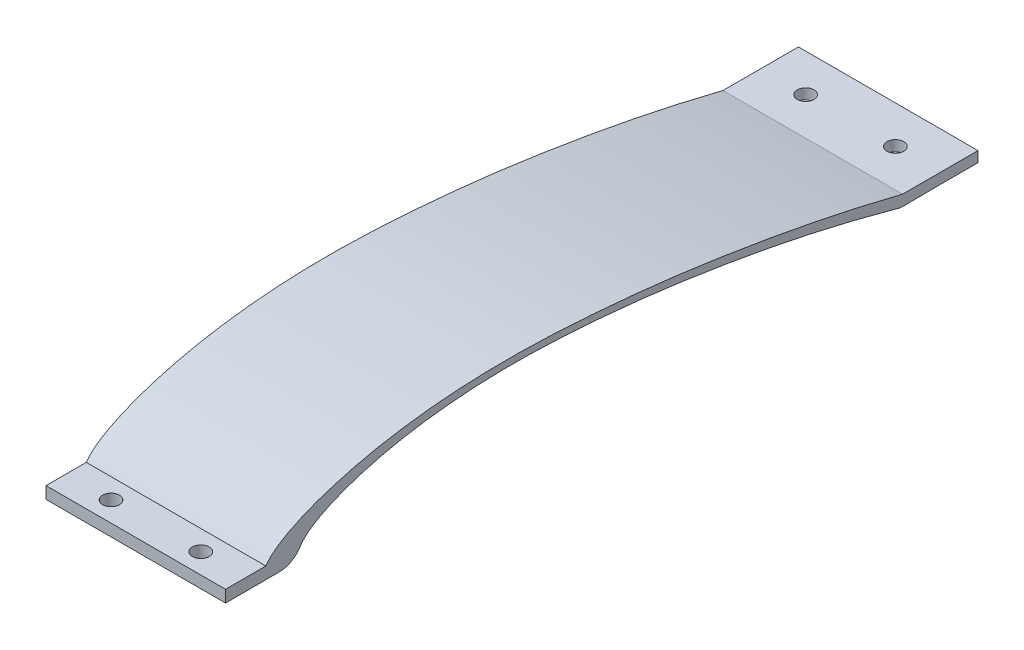
SolidWorks part; units mm, degrees
ref_plane "Front Plane" through (0, 0, 0) normal (0, 0, 1) x (1, 0, 0)
ref_plane "Top Plane" through (0, 0, 0) normal (0, 1, 0) x (1, 0, 0)
ref_plane "Right Plane" through (0, 0, 0) normal (1, 0, 0) x (0, 0, -1)
sketch "Sketch1" plane through (0, 0, 0) normal (1, 0, 0) x (0, 0, -1)
  arc A0 (-72.8391, -1.9598) -> (-75.0988, -4.0819) centre (-71.973, -5.1462) ccw
  spline S0 degree 3 poles (-72.8391, -1.9598) (-71.5193, -1.6011) (-70.1992, -1.244) (-67.557, -0.546) (-66.2347, -0.2062) (-62.2642, 0.7846) (-59.6128, 1.4106) (-54.3023, 2.6025) (-51.6431, 3.1671) (-46.3164, 4.2323) (-43.6489, 4.7326) (-38.3066, 5.6755) (-35.6319, 6.1188) (-30.2754, 6.9512) (-27.5936, 7.3389) (-19.535, 8.3999) (-14.1447, 8.9674) (-3.3295, 9.8307) (2.0964, 10.1191) (10.2856, 10.1582) (13.0238, 10.105) (17.1472, 9.8987) (18.5265, 9.8086) (21.2804, 9.5837) (22.6534, 9.449) (25.391, 9.133) (26.7556, 8.9518) (29.4761, 8.5409) (30.8319, 8.3111) (34.8834, 7.5325) (37.5622, 6.89) (41.5421, 5.7133) (42.8637, 5.2886) (45.453, 4.3284) (46.7237, 3.7932) (48.5836, 2.8839) (49.1954, 2.5618) (50.0944, 2.0358) (50.3918, 1.853) (50.9734, 1.4715) (51.2571, 1.2716) (51.8025, 0.8441) (52.0644, 0.6166) (52.5647, 0.1317) (52.8032, -0.1254) (53.2393, -0.6669) (53.439, -0.9532) (53.7755, -1.5678) (53.909, -1.8892) (54.0242, -2.4047) (54.0471, -2.5775) (54.0569, -2.9255) (54.0433, -3.1029) (53.9767, -3.4453) (53.9241, -3.6108) (53.7857, -3.9319) (53.7, -4.0864) (53.5079, -4.3759) (53.4007, -4.5126) (53.1684, -4.7729) (53.043, -4.8965) (52.653, -5.2424) (52.3721, -5.4443) (51.7759, -5.8001) (51.4587, -5.952) (50.8171, -6.2068) (50.4898, -6.312) (49.5008, -6.6028) (48.8306, -6.7592) (47.4738, -7.0165) (46.7908, -7.1162) (45.4268, -7.2745) (44.7442, -7.3333) (42.6956, -7.4788) (41.3287, -7.5388) (38.5934, -7.6044) (37.225, -7.6101) (34.4872, -7.5897) (33.1179, -7.5654) (30.3786, -7.4968) (29.0085, -7.4513) (26.2696, -7.338) (24.9006, -7.2706) (22.1627, -7.1323) (20.7937, -7.0629) (18.0556, -6.9306) (16.6864, -6.8663) (12.579, -6.6726) (9.8408, -6.5418) (4.364, -6.2908) (1.6253, -6.1723) (-3.8528, -5.9507) (-6.592, -5.8456) (-14.8094, -5.522) (-20.2871, -5.2904) (-31.2446, -4.8828) (-36.7244, -4.7045) (-47.6869, -4.4208) (-53.1687, -4.3186) (-61.392, -4.1963) (-64.1331, -4.1572) (-69.6157, -4.1049) (-72.3572, -4.0945) (-75.0988, -4.0819) knots 0 0 0 0 0.015625 0.015625 0.03125 0.03125 0.0625 0.0625 0.09375 0.09375 0.125 0.125 0.15625 0.15625 0.1875 0.1875 0.25 0.25 0.3125 0.3125 0.34375 0.34375 0.359375 0.359375 0.375 0.375 0.390625 0.390625 0.40625 0.40625 0.4375 0.4375 0.453125 0.453125 0.46875 0.46875 0.476563 0.476563 0.480469 0.480469 0.484375 0.484375 0.488281 0.488281 0.492188 0.492188 0.496094 0.496094 0.5 0.5 0.501953 0.501953 0.503906 0.503906 0.505859 0.505859 0.507813 0.507813 0.509766 0.509766 0.511719 0.511719 0.515625 0.515625 0.519531 0.519531 0.523438 0.523438 0.53125 0.53125 0.539063 0.539063 0.546875 0.546875 0.5625 0.5625 0.578125 0.578125 0.59375 0.59375 0.609375 0.609375 0.625 0.625 0.640625 0.640625 0.65625 0.65625 0.6875 0.6875 0.71875 0.71875 0.75 0.75 0.8125 0.8125 0.875 0.875 0.9375 0.9375 0.96875 0.96875 1 1 1 1
sketch "Sketch2" plane through (0, 0, 0) normal (1, 0, 0) x (0, 0, -1)
  line L0 (61.5517, -3.3211) -> (69.1717, -3.3211)
  line L1 (69.1717, -3.3211) -> (69.1717, -0.7811)
  line L2 (69.1717, -0.7811) -> (60.631, -0.7811)
  line L3 (61.5517, -3.3211) -> (54.0119, -3.2643)
  line L4 (-73.6502, -2.3019) -> (-82.9469, -2.2318)
  line L5 (-82.9469, -2.2318) -> (-90.4992, -2.2318)
  line L6 (-74.4831, 0) -> (-90.4992, 0)
  line L7 (-90.4992, 0) -> (-90.4992, -2.2318)
  arc A0 (-72.8391, -1.9598) -> (-75.0988, -4.0819) centre (-71.973, -5.1462) ccw construction
  arc A2 (-72.8391, -1.9598) -> (-73.6502, -2.3019) centre (-71.973, -5.1462) ccw
  spline S1 degree 3 poles (-74.4831, 0) (-74.2951, 0.0473) (-74.107, 0.0944) (-70.9046, 0.8935) (-67.8852, 1.6063) (-61.8378, 2.9637) (-58.8095, 3.6066) (-52.7437, 4.8196) (-49.706, 5.3893) (-43.6224, 6.4631) (-40.5765, 6.9679) (-34.4767, 7.9158) (-31.4227, 8.3573) (-22.2458, 9.5655) (-16.1076, 10.2118) (-3.7915, 11.1949) (2.3874, 11.5233) (11.7129, 11.5679) (14.8311, 11.5073) (19.5267, 11.2723) (21.0974, 11.1698) (24.2335, 10.9136) (25.797, 10.7602) (28.9144, 10.4004) (30.4684, 10.194) (33.5664, 9.7261) (35.1104, 9.4645) (39.7242, 8.5778) (42.7747, 7.8461) (47.3069, 6.5061) (48.8119, 6.0224) (51.7604, 4.9291) (53.2075, 4.3196) (55.3255, 3.2841) (56.0221, 2.9173) (57.046, 2.3183) (57.3846, 2.1101) (58.0469, 1.6757) (58.3699, 1.4481) (58.9911, 0.9613) (59.2893, 0.7021) (59.8591, 0.15) (60.1307, -0.1428) (60.4657, -0.5589) (60.5499, -0.6688) (60.631, -0.7811) knots 0.0293 0.0293 0.0293 0.0293 0.03125 0.03125 0.0625 0.0625 0.09375 0.09375 0.125 0.125 0.15625 0.15625 0.1875 0.1875 0.25 0.25 0.3125 0.3125 0.34375 0.34375 0.359375 0.359375 0.375 0.375 0.390625 0.390625 0.40625 0.40625 0.4375 0.4375 0.453125 0.453125 0.46875 0.46875 0.476563 0.476563 0.480469 0.480469 0.484375 0.484375 0.488281 0.488281 0.492188 0.492188 0.493552 0.493552 0.493552 0.493552
  spline S3 degree 3 poles (-766.0488, 2906.1722) (-272.4875, -107.0731) (-173.9202, -28.6447) (-67.557, -0.546) (-66.2347, -0.2062) (-62.2642, 0.7846) (-59.6128, 1.4106) (-54.3023, 2.6025) (-51.6431, 3.1671) (-46.3164, 4.2323) (-43.6489, 4.7326) (-38.3066, 5.6755) (-35.6319, 6.1188) (-30.2754, 6.9512) (-27.5936, 7.3389) (-19.535, 8.3999) (-14.1447, 8.9674) (-3.3295, 9.8307) (2.0964, 10.1191) (10.2856, 10.1582) (13.0238, 10.105) (17.1472, 9.8987) (18.5265, 9.8086) (21.2804, 9.5837) (22.6534, 9.449) (25.391, 9.133) (26.7556, 8.9518) (29.4761, 8.5409) (30.8319, 8.3111) (34.8834, 7.5325) (37.5622, 6.89) (41.5421, 5.7133) (42.8637, 5.2886) (45.453, 4.3284) (46.7237, 3.7932) (48.5836, 2.8839) (49.1954, 2.5618) (50.0944, 2.0358) (50.3918, 1.853) (50.9734, 1.4715) (51.2571, 1.2716) (51.8025, 0.8441) (52.0644, 0.6166) (52.5647, 0.1317) (52.8032, -0.1254) (53.2393, -0.6669) (53.439, -0.9532) (53.7755, -1.5678) (53.909, -1.8892) (54.0242, -2.4047) (54.0471, -2.5775) (54.0569, -2.9255) (54.0433, -3.1029) (53.9767, -3.4453) (53.9241, -3.6108) (53.7857, -3.9319) (53.7, -4.0864) (53.5079, -4.3759) (53.4007, -4.5126) (53.1684, -4.7729) (53.043, -4.8965) (52.653, -5.2424) (52.3721, -5.4443) (51.7759, -5.8001) (51.4587, -5.952) (50.8171, -6.2068) (50.4898, -6.312) (49.5008, -6.6028) (48.8306, -6.7592) (47.4738, -7.0165) (46.7908, -7.1162) (45.4268, -7.2745) (44.7442, -7.3333) (42.6956, -7.4788) (41.3287, -7.5388) (38.5934, -7.6044) (37.225, -7.6101) (34.4872, -7.5897) (33.1179, -7.5654) (30.3786, -7.4968) (29.0085, -7.4513) (26.2696, -7.338) (24.9006, -7.2706) (22.1627, -7.1323) (20.7937, -7.0629) (18.0556, -6.9306) (16.6864, -6.8663) (12.579, -6.6726) (9.8408, -6.5418) (4.364, -6.2908) (1.6253, -6.1723) (-3.8528, -5.9507) (-6.592, -5.8456) (-14.8094, -5.522) (-20.2871, -5.2904) (-31.2446, -4.8828) (-36.7244, -4.7045) (-47.6869, -4.4208) (-53.1687, -4.3186) (-61.392, -4.1963) (-64.1331, -4.1572) (-219.8399, -2.6734) (-373.5636, -50.0746) (-479.5254, 2948.4313) knots -1.226732 -1.226732 -1.226732 -1.226732 0.015625 0.015625 0.03125 0.03125 0.0625 0.0625 0.09375 0.09375 0.125 0.125 0.15625 0.15625 0.1875 0.1875 0.25 0.25 0.3125 0.3125 0.34375 0.34375 0.359375 0.359375 0.375 0.375 0.390625 0.390625 0.40625 0.40625 0.4375 0.4375 0.453125 0.453125 0.46875 0.46875 0.476563 0.476563 0.480469 0.480469 0.484375 0.484375 0.488281 0.488281 0.492188 0.492188 0.496094 0.496094 0.5 0.5 0.501953 0.501953 0.503906 0.503906 0.505859 0.505859 0.507813 0.507813 0.509766 0.509766 0.511719 0.511719 0.515625 0.515625 0.519531 0.519531 0.523438 0.523438 0.53125 0.53125 0.539063 0.539063 0.546875 0.546875 0.5625 0.5625 0.578125 0.578125 0.59375 0.59375 0.609375 0.609375 0.625 0.625 0.640625 0.640625 0.65625 0.65625 0.6875 0.6875 0.71875 0.71875 0.75 0.75 0.8125 0.8125 0.875 0.875 0.9375 0.9375 0.96875 0.96875 2.712507 2.712507 2.712507 2.712507 only from (-72.8391, -1.9598) to (-75.0988, -4.0819) construction
  spline S4 degree 3 poles (-72.8391, -1.9598) (-71.5193, -1.6011) (-70.1992, -1.244) (-67.557, -0.546) (-66.2347, -0.2062) (-62.2642, 0.7846) (-59.6128, 1.4106) (-54.3023, 2.6025) (-51.6431, 3.1671) (-46.3164, 4.2323) (-43.6489, 4.7326) (-38.3066, 5.6755) (-35.6319, 6.1188) (-30.2754, 6.9512) (-27.5936, 7.3389) (-19.535, 8.3999) (-14.1447, 8.9674) (-3.3295, 9.8307) (2.0964, 10.1191) (10.2856, 10.1582) (13.0238, 10.105) (17.1472, 9.8987) (18.5265, 9.8086) (21.2804, 9.5837) (22.6534, 9.449) (25.391, 9.133) (26.7556, 8.9518) (29.4761, 8.5409) (30.8319, 8.3111) (34.8834, 7.5325) (37.5622, 6.89) (41.5421, 5.7133) (42.8637, 5.2886) (45.453, 4.3284) (46.7237, 3.7932) (48.5836, 2.8839) (49.1954, 2.5618) (50.0944, 2.0358) (50.3918, 1.853) (50.9734, 1.4715) (51.2571, 1.2716) (51.8025, 0.8441) (52.0644, 0.6166) (52.5647, 0.1317) (52.8032, -0.1254) (53.2393, -0.6669) (53.439, -0.9532) (53.7755, -1.5678) (53.909, -1.8892) (54.0242, -2.4047) (54.0471, -2.5775) (54.0568, -2.9221) (54.0438, -3.0961) (54.0119, -3.2643) knots 0 0 0 0 0.015625 0.015625 0.03125 0.03125 0.0625 0.0625 0.09375 0.09375 0.125 0.125 0.15625 0.15625 0.1875 0.1875 0.25 0.25 0.3125 0.3125 0.34375 0.34375 0.359375 0.359375 0.375 0.375 0.390625 0.390625 0.40625 0.40625 0.4375 0.4375 0.453125 0.453125 0.46875 0.46875 0.476563 0.476563 0.480469 0.480469 0.484375 0.484375 0.488281 0.488281 0.492188 0.492188 0.496094 0.496094 0.5 0.5 0.501953 0.501953 0.503869 0.503869 0.503869 0.503869
  dimension "D1" = 7.62
  dimension "D2" = 2.54
extrude "Boss-Extrude1" add sketch "Sketch2" along normal blind 38.1
ref_plane "Plane1" through (0, -0.7811, 0) normal (0, 1, 0) x (1, 0, 0)
sketch "Sketch3" plane through (0, -0.7811, 0) normal (0, 1, 0) x (1, 0, 0)
  line L0 (0, 64.9013) -> (19.05, 64.9013)
  line L1 (0, 69.1717) -> (0, 60.631) construction
  line L3 (0, 64.9013) -> (19.05, 64.9013)
  line L4 (19.05, 64.9013) -> (19.05, 69.1717)
  line L5 (38.1, 69.1717) -> (0, 69.1717) construction
  circle A0 centre (9.525, 64.9013) radius 1.778
  circle A1 centre (28.575, 64.9013) radius 1.778
  dimension "D1" = 3.556
extrude "Cut-Extrude1" cut sketch "Sketch3" against normal blind 38.1 contours L3 A0 | L3 A0 | A1
sketch "Sketch4" plane through (0, -0.7811, 0) normal (0, 1, 0) x (1, 0, 0)
  circle A0 centre (9.525, -82.4912) radius 1.778
  circle A1 centre (28.575, -82.4912) radius 1.778
  dimension "D1" = 3.556
extrude "Cut-Extrude3" cut sketch "Sketch4" against normal blind 28.448 and the other way blind 11.938
move or copy body "Body-Move/Copy1" bodies to move or copy 104 copy no rotation origin (19.05, 0, 10.6637) rotation axis (0, 1, 0) rotation angle 180
fillet "Fillet1" radius 5.08 1 edges at (19.05, -3.2643, 75.3394)
fillet "Fillet2" radius 5.08 1 edges at (19.05, -2.3019, -52.3227)
